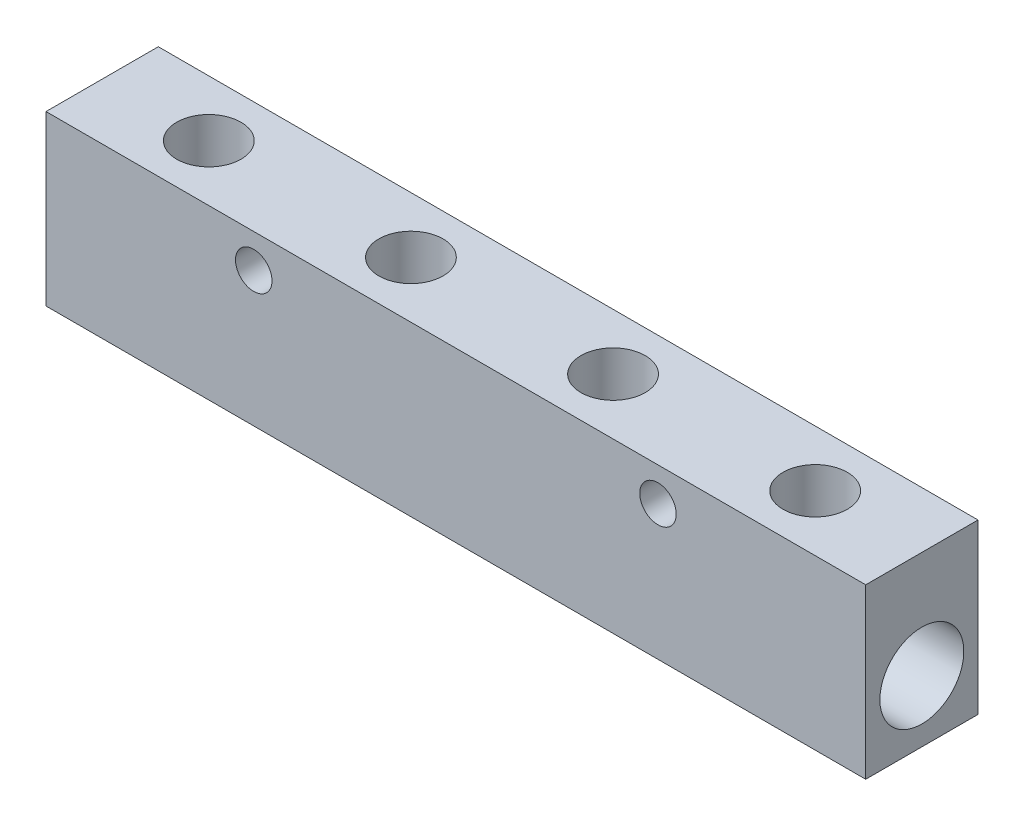
SolidWorks part; units mm, degrees
ref_plane "Front Plane" through (0, 0, 0) normal (0, 0, 1) x (1, 0, 0)
ref_plane "Top Plane" through (0, 0, 0) normal (0, 1, 0) x (1, 0, 0)
ref_plane "Right Plane" through (0, 0, 0) normal (1, 0, 0) x (0, 0, -1)
sketch "Sketch1" plane through (0, 0, 0) normal (0, 1, 0) x (1, 0, 0)
  line L1 (-73, -10) -> (73, -10)
  line L2 (-73, -10) -> (-73, 10)
  line L3 (-73, 10) -> (73, 10)
  line L4 (73, -10) -> (73, 10)
  line L5 (-73, -10) -> (73, 10) construction
  line L6 (-73, 10) -> (73, -10) construction
  point P0 (0, 0)
extrude "Boss-Extrude1" add sketch "Sketch1" along normal blind 30
sketch "Sketch2" plane through (0, 0, 10) normal (0, 0, 1) x (1, 0, 0)
  line L0 (-73, 30) -> (73, 30) construction
  line L1 (-73, 30) -> (-73, 0) construction
  line L2 (73, 30) -> (73, 0) construction
  circle A0 centre (-36, 24) radius 3.25
  circle A1 centre (36, 24) radius 3.25
  dimension "D1" = 6
  dimension "D3" = 6.5
  dimension "D4" = 6.5
  dimension "D2" = 37
  dimension "D5" = 37
  dimension "D6" = 6
extrude "Cut-Extrude1" cut sketch "Sketch2" against normal blind 30
sketch "Sketch3" plane through (-73, 0, 0) normal (-1, 0, 0) x (0, 0, 1)
  line L4 (-10, 0) -> (10, 0) construction
  circle A1 centre (0, 11) radius 7.475
  dimension "D1" = 14.95
  dimension "D2" = 11
extrude "Cut-Extrude2" cut sketch "Sketch3" against normal through all
sketch "Sketch4" plane through (0, 30, 0) normal (0, 1, 0) x (1, 0, 0)
  line L0 (-73, 10) -> (-73, -10) construction
  line L1 (73, 10) -> (-73, 10) construction
  line L2 (73, -10) -> (73, 10) construction
  line L3 (-73, -10) -> (73, -10) construction
  circle A0 centre (-54, 0) radius 5.7225
  circle A2 centre (-18, 0) radius 5.7225
  circle A3 centre (18, 0) radius 5.7225
  circle A4 centre (54, 0) radius 5.7225
  dimension "D2" = 11.445
  dimension "D4" = 11.445
  dimension "D5" = 11.445
  dimension "D6" = 11.445
  dimension "D1" = 19
  dimension "D3" = 10
  dimension "D7" = 19
  dimension "D8" = 10
  dimension "D9" = 10
  dimension "D10" = 10
  dimension "D11" = 36
  dimension "D12" = 36
extrude "Cut-Extrude3" cut sketch "Sketch4" against normal blind 15
